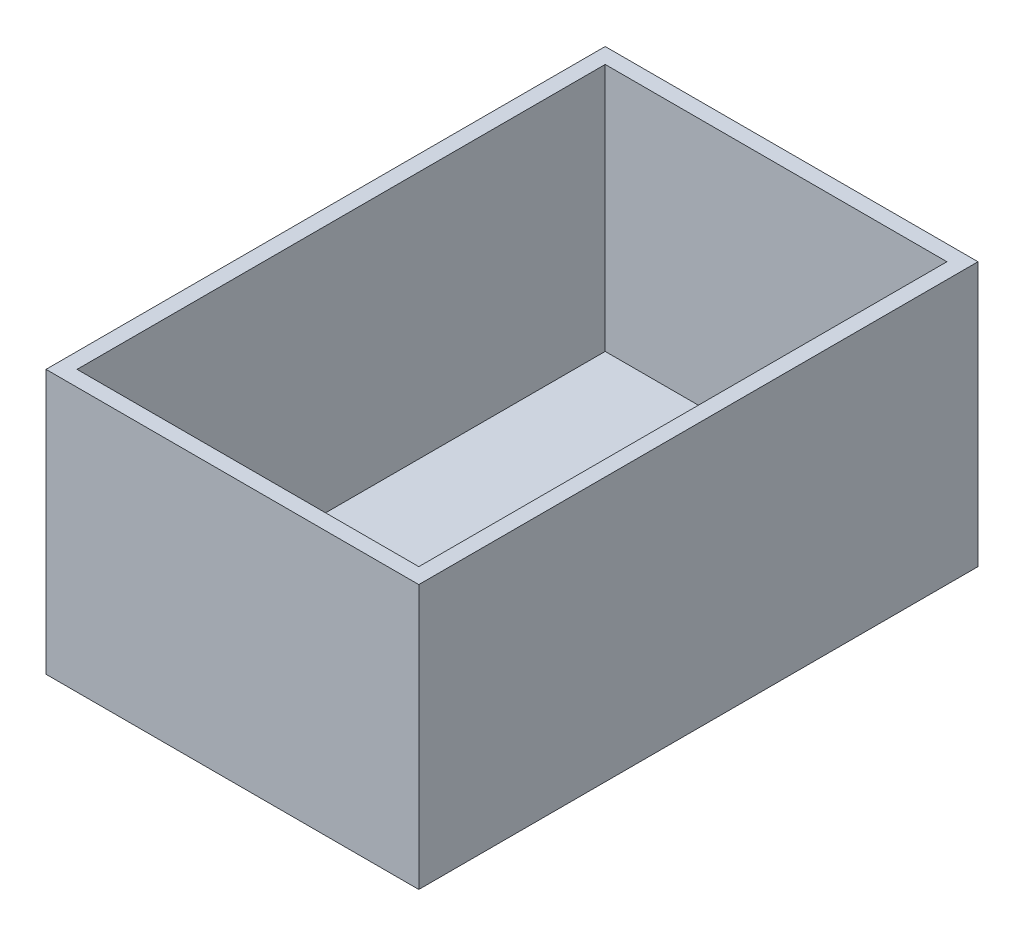
SolidWorks part; units mm, degrees
ref_plane "Front Plane" through (0, 0, 0) normal (0, 0, 1) x (1, 0, 0)
ref_plane "Top Plane" through (0, 0, 0) normal (0, 1, 0) x (1, 0, 0)
ref_plane "Right Plane" through (0, 0, 0) normal (1, 0, 0) x (0, 0, -1)
sketch "Sketch1" plane through (0, 0, 0) normal (0, 1, 0) x (1, 0, 0)
  line L1 (-60, 90) -> (60, 90)
  line L2 (-60, 90) -> (-60, -90)
  line L3 (-60, -90) -> (60, -90)
  line L4 (60, 90) -> (60, -90)
  line L5 (-60, 90) -> (60, -90) construction
  line L6 (-60, -90) -> (60, 90) construction
  point P0 (0, 0)
  dimension "D1" = 120
  dimension "D2" = 180
extrude "Boss-Extrude1" add sketch "Sketch1" along normal blind 5
sketch "Sketch2" plane through (0, 5, 0) normal (0, 1, 0) x (1, 0, 0)
  line L1 (-60, 90) -> (60, 90)
  line L2 (-60, 90) -> (-60, -90)
  line L3 (-60, -90) -> (60, -90)
  line L4 (60, 90) -> (60, -90)
  line L5 (-60, 90) -> (60, -90) construction
  line L6 (-60, -90) -> (60, 90) construction
  line L7 (-55, 85) -> (55, 85)
  line L8 (-55, 85) -> (-55, -85)
  line L9 (-55, -85) -> (55, -85)
  line L10 (55, 85) -> (55, -85)
  line L11 (-55, 85) -> (55, -85) construction
  line L12 (-55, -85) -> (55, 85) construction
  point P0 (0, 0)
  point P7 (0, 0)
  dimension "D1" = 5
  dimension "D2" = 5
extrude "Boss-Extrude2" add sketch "Sketch2" along normal blind 80
